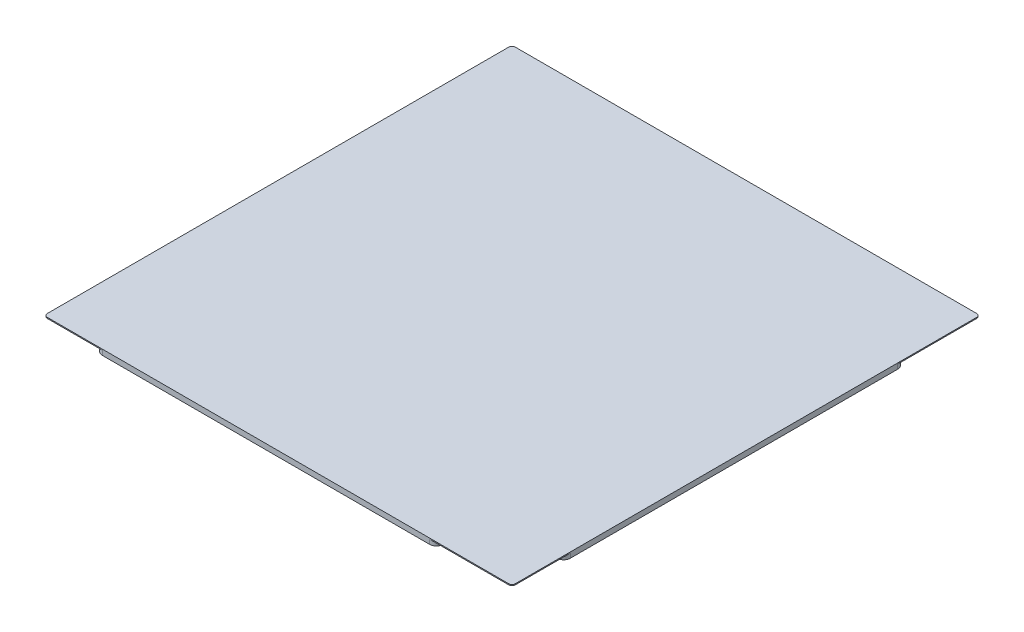
SolidWorks part; units mm, degrees
material "Kapton"
ref_plane "Front Plane" through (0, 0, 0) normal (0, 0, 1) x (1, 0, 0)
ref_plane "Top Plane" through (0, 0, 0) normal (0, 1, 0) x (1, 0, 0)
ref_plane "Right Plane" through (0, 0, 0) normal (1, 0, 0) x (0, 0, -1)
sketch "Sketch1" plane through (0, 0, 0) normal (0, 1, 0) x (1, 0, 0)
  line L1 (-68.35, -68.35) -> (68.35, -68.35)
  line L2 (-68.35, -68.35) -> (-68.35, 68.35)
  line L3 (-68.35, 68.35) -> (68.35, 68.35)
  line L4 (68.35, -68.35) -> (68.35, 68.35)
  line L5 (-68.35, -68.35) -> (68.35, 68.35) construction
  line L6 (-68.35, 68.35) -> (68.35, -68.35) construction
  point P0 (0, 0)
  dimension "D1" = 136.7
extrude "Boss-Extrude1" add sketch "Sketch1" along normal mid plane 0.3
sketch "Sketch2" plane through (0, -0.15, 0) normal (0, -1, 0) x (1, 0, 0)
  line L0 (69.85, -68.35) -> (43.2833, -68.35) construction
  line L1 (68.35, -68.35) -> (-68.35, -68.35) construction
  line L2 (43.2833, -68.35) -> (13.2833, -68.35) construction
  line L3 (13.2833, -68.35) -> (-13.2833, -68.35) construction
  line L4 (-13.2833, -68.35) -> (-43.2833, -68.35) construction
  line L5 (-43.2833, -68.35) -> (-69.85, -68.35) construction
  line L6 (43.2833, -68.35) -> (53.2833, -54.85) construction
  line L7 (-68.35, -68.35) -> (-68.35, 68.35) construction
  line L8 (68.35, 68.35) -> (68.35, -68.35) construction
  line L9 (-54.85, -53.2833) -> (-68.35, -53.2833)
  line L10 (53.2833, -54.85) -> (-46.2833, -54.85)
  line L11 (53.2833, -54.85) -> (53.2833, -68.35)
  line L12 (53.2833, -68.35) -> (-46.2833, -68.35)
  line L13 (-46.2833, -54.85) -> (-46.2833, -68.35)
  line L14 (-54.85, -53.2833) -> (-54.85, 46.2833)
  line L15 (-54.85, 46.2833) -> (-68.35, 46.2833)
  line L16 (-68.35, -53.2833) -> (-68.35, 46.2833)
  line L17 (-53.2833, 54.85) -> (-53.2833, 68.35)
  line L18 (-53.2833, 54.85) -> (46.2833, 54.85)
  line L19 (46.2833, 54.85) -> (46.2833, 68.35)
  line L20 (-53.2833, 68.35) -> (46.2833, 68.35)
  line L21 (54.85, 53.2833) -> (68.35, 53.2833)
  line L22 (54.85, 53.2833) -> (54.85, -46.2833)
  line L23 (54.85, -46.2833) -> (68.35, -46.2833)
  line L24 (68.35, 53.2833) -> (68.35, -46.2833)
  line L25 (-68.35, 68.35) -> (68.35, 68.35) construction
  point P33 (0, 0)
  dimension "D1" = 30
  dimension "D2" = 13.5
  dimension "D3" = 10
  dimension "D4" = 1.5
  dimension "D5" = 1.5
  dimension "D6" = 3
  dimension "D7" = 4
extrude "Boss-Extrude2" add sketch "Sketch2" along normal blind 1.3
fillet "Fillet1" radius 2 16 edges at (53.2833, -0.8, -54.85) (-46.2833, -0.8, -54.85) (-46.2833, -0.8, -68.35) (-68.35, -0.8, -53.2833) (-54.85, -0.8, -53.2833) (-54.85, -0.8, 46.2833) (-68.35, -0.8, 46.2833) (-53.2833, -0.8, 68.35) (-53.2833, -0.8, 54.85) (46.2833, -0.8, 54.85) (46.2833, -0.8, 68.35) (53.2833, -0.8, -68.35) (54.85, -0.8, 53.2833) (68.35, -0.8, 53.2833) (68.35, -0.8, -46.2833) (54.85, -0.8, -46.2833)
fillet "Fillet2" radius 1 4 edges at (-68.35, 0, 68.35) (-68.35, 0, -68.35) (68.35, 0, -68.35) (68.35, 0, 68.35)
equation "\"panel_width\"= 5.5in"
equation "\"finger_joint_width\" = 30mm"
equation "\"D1@Sketch1\"=\"panel_width\"-3"
equation "\"D1@Sketch2\"=\"finger_joint_width\""
